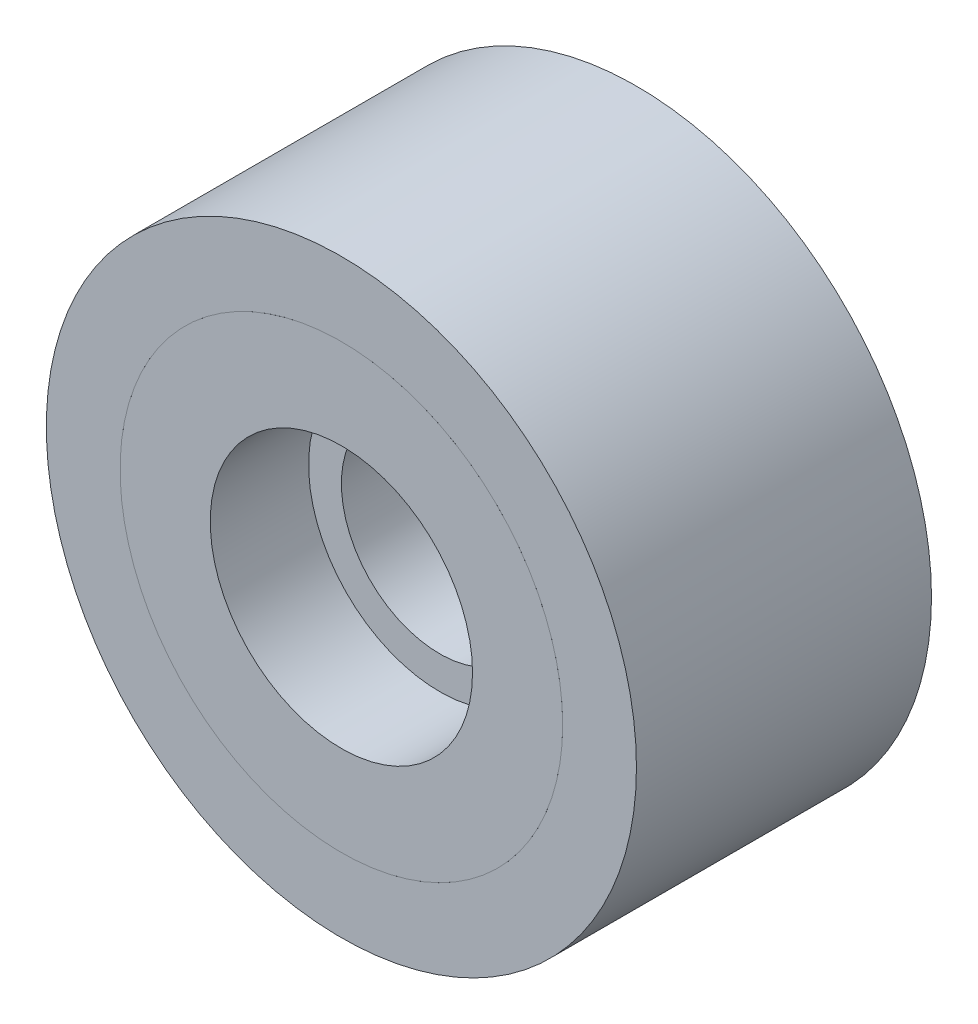
SolidWorks part; units mm, degrees
ref_plane "Front Plane" through (0, 0, 0) normal (0, 0, 1) x (1, 0, 0)
ref_plane "Top Plane" through (0, 0, 0) normal (0, 1, 0) x (1, 0, 0)
ref_plane "Right Plane" through (0, 0, 0) normal (1, 0, 0) x (0, 0, -1)
sketch "Sketch1" plane through (0, 0, 0) normal (1, 0, 0) x (0, 0, -1)
  line L0 (0, 0) -> (141.0669, 0) construction
  line L4 (0, 30) -> (3, 30) construction
  line L5 (3, 30) -> (3, 27) construction
  line L13 (3, 36) -> (39, 36) construction
  line L15 (3, 27) -> (39, 27)
  line L16 (39, 27) -> (39, 30) construction
  line L17 (39, 30) -> (42, 30) construction
  line L18 (0, 30) -> (0, 16) construction
  line L19 (3, 16) -> (15, 16)
  line L20 (15, 16) -> (15, 12)
  line L21 (42, 27) -> (42, 16) construction
  line L22 (39, 16) -> (27, 16)
  line L23 (27, 16) -> (27, 12)
  line L24 (27, 12) -> (15, 12)
  line L25 (39, 27) -> (42, 27) construction
  line L26 (42, 30) -> (42, 27) construction
  line L27 (39, 27) -> (39, 16)
  line L28 (39, 16) -> (42, 16) construction
  line L29 (3, 27) -> (0, 27) construction
  line L30 (3, 27) -> (3, 16)
  line L31 (0, 16) -> (3, 16) construction
  dimension "D2" = 36
  dimension "D3" = 3
  dimension "D4" = 3
  dimension "D5" = 12
  dimension "D6" = 16
  dimension "D7" = 12
  dimension "D8" = 12
  dimension "D9" = 36
  dimension "D10" = 9
revolve "Revolve1" add sketch "Sketch1" angle 360 about L0
sketch "Sketch2" plane through (0, 0, -39) normal (0, 0, 1) x (1, 0, 0)
  line L0 (0, 21) -> (0, 0) construction
  circle A0 centre (0, 21) radius 1.5
  circle A6 centre (18.1865, 10.5) radius 1.5
  circle A7 centre (18.1865, -10.5) radius 1.5
  circle A8 centre (0, -21) radius 1.5
  circle A9 centre (-18.1865, -10.5) radius 1.5
  circle A10 centre (-18.1865, 10.5) radius 1.5
  point P16 (0, 0)
  dimension "D1" = 3
  dimension "D2" = 21
  dimension "D3" = 6
sketch "Sketch3" plane through (0, 0, 0) normal (1, 0, 0) x (0, 0, -1)
  line L0 (38.999, 36) -> (3.001, 36)
  line L1 (3.001, 36) -> (3.001, 27.001)
  line L2 (3.001, 27.001) -> (38.999, 27.001)
  line L3 (38.999, 27.001) -> (38.999, 36)
  line L4 (39, 27) -> (3, 27) construction
  line L5 (39, 27) -> (3, 27) construction
  line L7 (0, 0) -> (42, 0) construction
  point P6 (42, 0)
  dimension "D1" = 0.001
  dimension "D2" = 0.001
  dimension "D3" = 35.998
  dimension "D4" = 36
revolve "Revolve2" add sketch "Sketch3" angle 360 about L7
extrude "Cut-Extrude1" cut sketch "Sketch2" along normal blind 30
